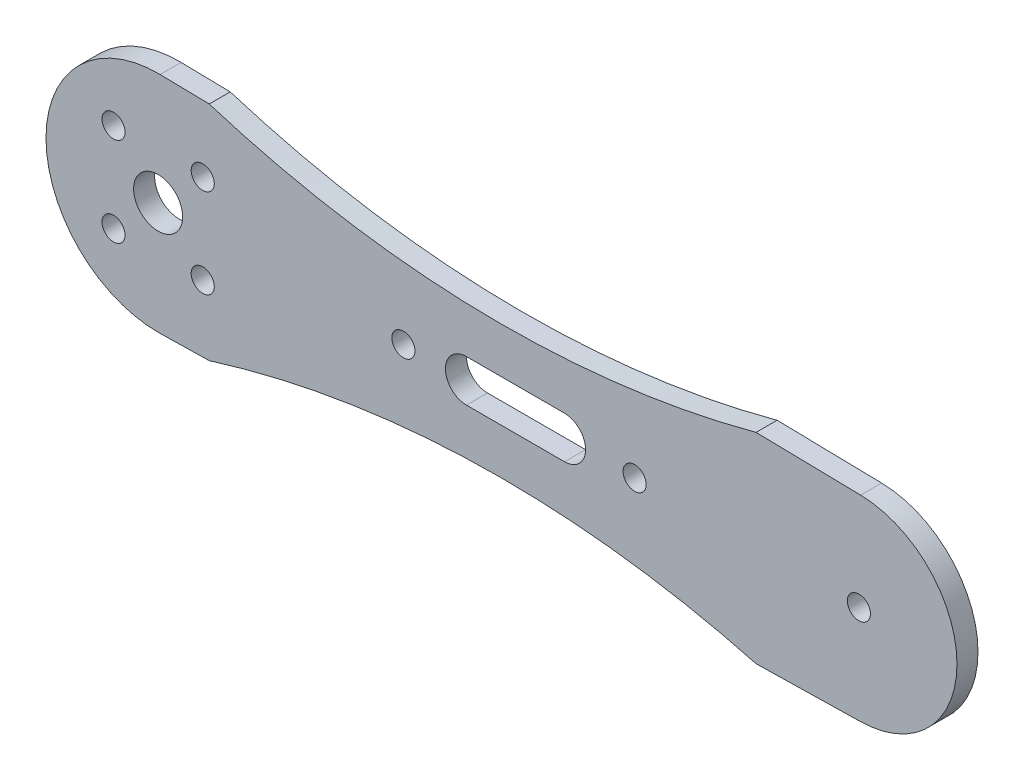
SolidWorks part; units mm, degrees
ref_plane "Спереди" through (0, 0, 0) normal (0, 0, 1) x (1, 0, 0)
ref_plane "Сверху" through (0, 0, 0) normal (0, 1, 0) x (1, 0, 0)
ref_plane "Справа" through (0, 0, 0) normal (1, 0, 0) x (0, 0, -1)
other "Configuration Table"
sketch "Eskiz_kontur" plane through (0, 0, 0) normal (0, 0, 1) x (1, 0, 0)
  line L0 (7.2912, -15.8573) -> (0.2792, -15.9976)
  line L1 (100.2443, -13.9979) -> (85.3309, -14.2962)
  line L2 (0.2792, 15.9976) -> (7.2912, 15.8573)
  line L3 (85.3309, 14.2962) -> (100.2443, 13.9979)
  line L4 (58, 3) -> (44, 3)
  line L5 (44, -3) -> (58, -3)
  arc A0 (85.3309, -14.2962) -> (7.2912, -15.8573) centre (49, -149.5) ccw
  arc A1 (0.2792, -15.9976) -> (0.2792, 15.9976) centre (0, 0) cw
  arc A2 (100.2443, 13.9979) -> (100.2443, -13.9979) centre (99.9999, 0) cw
  arc A3 (7.2912, 15.8573) -> (85.3309, 14.2962) centre (49, 149.5) ccw
  arc A4 (44, 3) -> (44, -3) centre (44, 0) ccw
  arc A5 (58, -3) -> (58, 3) centre (58, 0) ccw
extrude "Plastina" add sketch "Eskiz_kontur" along normal blind 3
sketch "Eskiz_otverstiya" plane through (0, 0, 0) normal (0, 0, 1) x (1, 0, 0)
  circle A0 centre (-6.364, -6.364) radius 1.65
  circle A1 centre (6.364, -6.364) radius 1.65
  circle A2 centre (0, 0) radius 3.5
  circle A3 centre (35, 0) radius 1.65
  circle A4 centre (-6.364, 6.364) radius 1.65
  circle A5 centre (6.364, 6.364) radius 1.65
  circle A6 centre (68, 0) radius 1.65
  circle A7 centre (100, 0) radius 1.65
  dimension "d1" = 3.3
  dimension "d2" = 3.3
  dimension "d3" = 7
  dimension "d4" = 3.3
  dimension "d5" = 3.3
  dimension "d6" = 3.3
  dimension "d7" = 3.3
  dimension "d8" = 3.3
extrude "Otverstiya" cut sketch "Eskiz_otverstiya" against normal through all and the other way through all
equation "\"T3\" = 3"
equation "\"T5\" = 5"
equation "\"D_M3\" = 3.3"
equation "\"D_M2\" = 2.2"
equation "\"D_M3_TAP\" = 2.5"
equation "\"D_M4\" = 4.5"
equation "\"L1\" = 100"
equation "\"L2\" = 100"
equation "\"D1@Plastina\" = \"T3\""
equation "\"d1@Eskiz_otverstiya\" = \"D_M3\""
equation "\"d2@Eskiz_otverstiya\" = \"D_M3\""
equation "\"d4@Eskiz_otverstiya\" = \"D_M3\""
equation "\"d5@Eskiz_otverstiya\" = \"D_M3\""
equation "\"d6@Eskiz_otverstiya\" = \"D_M3\""
equation "\"d7@Eskiz_otverstiya\" = \"D_M3\""
equation "\"d8@Eskiz_otverstiya\" = \"D_M3\""
